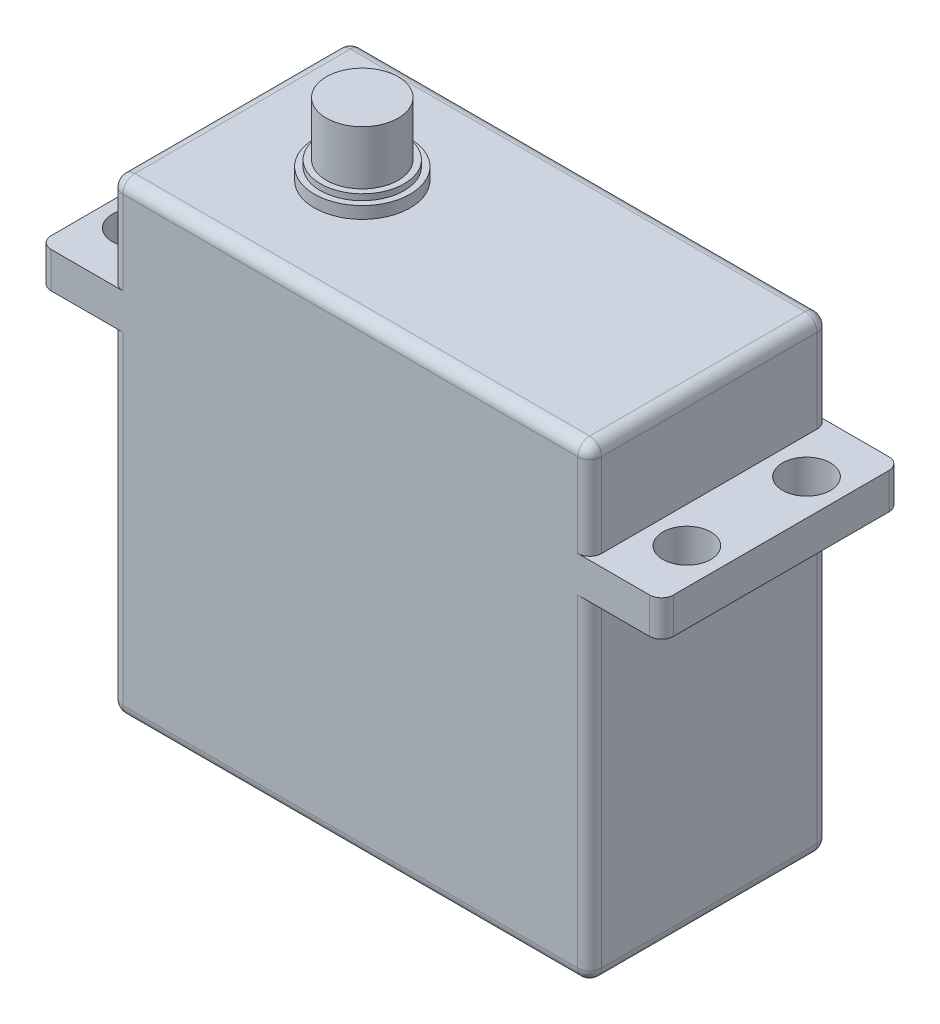
SolidWorks part; units mm, degrees
ref_plane "前视基准面" through (0, 0, 0) normal (0, 0, 1) x (1, 0, 0)
ref_plane "上视基准面" through (0, 0, 0) normal (0, 1, 0) x (1, 0, 0)
ref_plane "右视基准面" through (0, 0, 0) normal (1, 0, 0) x (0, 0, -1)
other "Configuration Table"
sketch "草图2" plane through (0, 0, 0) normal (0, 0, 1) x (1, 0, 0)
  line L1 (-20, 19.5) -> (20, 19.5)
  line L2 (-20, 19.5) -> (-20, -19.5)
  line L3 (-20, -19.5) -> (20, -19.5)
  line L4 (20, 19.5) -> (20, -19.5)
  line L5 (-20, 19.5) -> (20, -19.5) construction
  line L6 (-20, -19.5) -> (20, 19.5) construction
  point P0 (0, 0)
  dimension "D1" = 40
  dimension "D2" = 39
extrude "凸台-拉伸1" add sketch "草图2" along normal blind 20
sketch "草图3" plane through (0, 19.5, 0) normal (0, 1, 0) x (1, 0, 0)
  line L0 (-20, -10) -> (-23, -10)
  line L1 (-20, -20) -> (-20, 0) construction
  line L2 (-20, -10) -> (-9, -10)
  circle A0 centre (-9, -10) radius 4
  circle A1 centre (-9, -10) radius 3.5
  circle A2 centre (-9, -10) radius 3
extrude "凸台-拉伸2" add sketch "草图3" along normal blind 1 contours A0
sketch "草图4" plane through (0, 20.5, 0) normal (0, 1, 0) x (1, 0, 0)
  circle A0 centre (-9, -10) radius 3.5
  point P4 (0, 0)
extrude "凸台-拉伸3" add sketch "草图4" along normal blind 0.5
sketch "草图6" plane through (0, 21, 0) normal (0, 1, 0) x (1, 0, 0)
  circle A0 centre (-9, -10) radius 3
extrude "凸台-拉伸4" add sketch "草图6" along normal blind 4.5
sketch "草图7" plane through (-20, 0, 0) normal (-1, 0, 0) x (0, 0, 1)
  line L0 (20, 19.5) -> (20, 11.5)
  line L1 (20, 19.5) -> (20, -19.5) construction
  line L2 (0, -22) -> (0, 22) construction
  line L3 (20, 11.5) -> (0, 11.5)
  line L4 (20, 11.5) -> (20, 8.5)
  line L5 (20, 8.5) -> (0, 8.5)
  line L6 (0, 11.5) -> (0, 8.5)
  line M3 (0, 19.5) -> (0, -19.5)
  line M5 (20, -19.5) -> (20, 19.5)
  dimension "D1" = 3
  dimension "D2" = 8
extrude "凸台-拉伸5" add sketch "草图7" along normal blind 6 contours L5 L3 M5 M3
sketch "草图8" plane through (0, 11.5, 0) normal (0, 1, 0) x (1, 0, 0)
  line L0 (-20, -10) -> (-23, -10)
  line L1 (-20, -20) -> (-20, 0) construction
  circle A0 centre (-23, -14.8808) radius 2
  circle A1 centre (-23, -4.8808) radius 2
  point P8 (-23, -3.9059)
  dimension "D1" = 10
extrude "切除-拉伸1" cut sketch "草图8" against normal blind 6 contours A1 | A0
mirror "镜向3" about plane through (0, 0, 0) normal (1, 0, 0) of "凸台-拉伸5", "切除-拉伸1"
fillet "圆角6" radius 1 1 edges at (-20, -19.5, 10)
fillet "圆角7" radius 1 1 edges at (20, -19.5, 10)
fillet "圆角8" radius 1 1 edges at (20, 19.5, 10)
fillet "圆角9" radius 1 1 edges at (-20, 19.5, 10)
fillet "圆角10" radius 1 2 edges at (-26, 10, 0) (-26, 10, 20)
fillet "圆角11" radius 1 2 edges at (26, 10, 0) (26, 10, 20)
fillet "圆角12" radius 1 20 edges at (20, 15, 0) (20, 15, 20) (19.7071, 19.2071, 20) (19.7071, 19.2071, 0) (0, 19.5, 0) (0, 19.5, 20) (-19.7071, 19.2071, 20) (-19.7071, 19.2071, 0) (20, -5, 20) (20, -5, 0) (19.7071, -19.2071, 20) (19.7071, -19.2071, 0) (0, -19.5, 0) (0, -19.5, 20) (-19.7071, -19.2071, 20) (-19.7071, -19.2071, 0) (-20, 15, 20) (-20, 15, 0) (-20, -5, 0) (-20, -5, 20)
